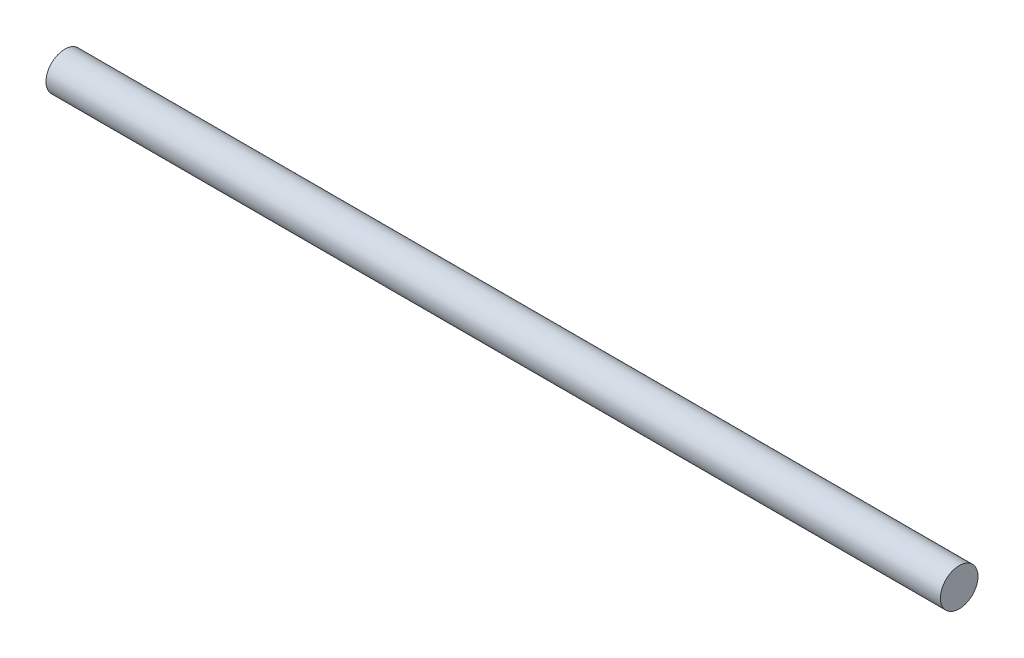
SolidWorks part; units mm, degrees
ref_plane "Front Plane" through (0, 0, 0) normal (0, 0, 1) x (1, 0, 0)
ref_plane "Top Plane" through (0, 0, 0) normal (0, 1, 0) x (1, 0, 0)
ref_plane "Right Plane" through (0, 0, 0) normal (1, 0, 0) x (0, 0, -1)
sketch "Sketch1" plane through (0, 0, 0) normal (1, 0, 0) x (0, 0, -1)
  circle A0 centre (0, 0) radius 1.25
  dimension "D1" = 2.5
extrude "Boss-Extrude1" add sketch "Sketch1" along normal blind 59.5
